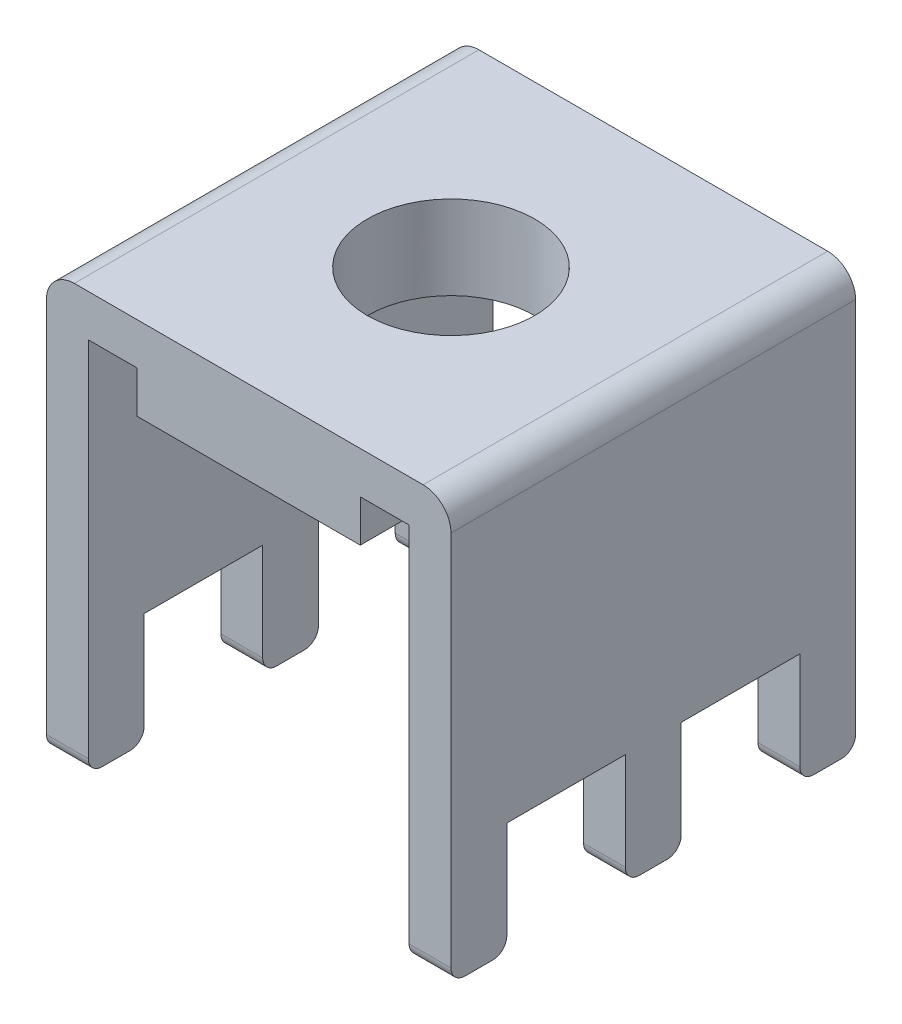
SolidWorks part; units mm, degrees
ref_plane "Front Plane" through (0, 0, 0) normal (0, 0, 1) x (1, 0, 0)
ref_plane "Top Plane" through (0, 0, 0) normal (0, 1, 0) x (1, 0, 0)
ref_plane "Right Plane" through (0, 0, 0) normal (1, 0, 0) x (0, 0, -1)
sketch "Sketch1" plane through (0, 0, 0) normal (0, 0, 1) x (1, 0, 0)
  line L0 (0, 0) -> (-1.5, 0)
  line L1 (-1.5, 0) -> (-1.5, 14)
  line L2 (-0.5, 15) -> (12, 15)
  line L3 (13, 14) -> (13, 0)
  line L4 (13, 0) -> (11.5, 0)
  line L5 (11.5, 0) -> (11.5, 13.5)
  line L6 (11.5, 13.5) -> (9.75, 13.5)
  line L7 (9.75, 13.5) -> (9.75, 12)
  line L8 (9.75, 12) -> (1.75, 12)
  line L9 (1.75, 12) -> (1.75, 13.5)
  line L10 (1.75, 13.5) -> (0, 13.5)
  line L11 (0, 13.5) -> (0, 0)
  arc A0 (12, 15) -> (13, 14) centre (12, 14) cw
  arc A1 (-1.5, 14) -> (-0.5, 15) centre (-0.5, 14) cw
  dimension "D8" = 1
  dimension "D1" = 1.5
  dimension "D2" = 1.5
  dimension "D3" = 14.5
  dimension "D4" = 15
  dimension "D5" = 1.5
  dimension "D6" = 3
  dimension "D7" = 8
extrude "Boss-Extrude1" add sketch "Sketch1" along normal blind 14.5
sketch "Sketch2" plane through (13, 0, 0) normal (1, 0, 0) x (0, 0, -1)
  line L0 (-14.5, 0) -> (0, 0) construction
  line L1 (-12.5, 0) -> (-8.25, 0)
  line L2 (-12.5, 0) -> (-12.5, 4)
  line L3 (-12.5, 4) -> (-8.25, 4)
  line L4 (-8.25, 0) -> (-8.25, 4)
  line L5 (0, 0) -> (0, 14) construction
  line L6 (-6.25, 0) -> (-2, 0)
  line L7 (-6.25, 0) -> (-6.25, 4)
  line L8 (-6.25, 4) -> (-2, 4)
  line L9 (-2, 0) -> (-2, 4)
  line L10 (-14.5, 0) -> (-14.5, 14) construction
  dimension "D1" = 2
  dimension "D2" = 2
  dimension "D3" = 2
  dimension "D4" = 4
extrude "Cut-Extrude1" cut sketch "Sketch2" against normal up to surface (14.5 mm away) up to face at (-1.5, 7, 7.25)
fillet "Fillet1" radius 0.5 12 edges at (-0.75, 0, 14.5) (-0.75, 0, 12.5) (-0.75, 0, 2) (-0.75, 0, 0) (-0.75, 0, 8.25) (-0.75, 0, 6.25) (12.25, 0, 0) (12.25, 0, 6.25) (12.25, 0, 2) (12.25, 0, 8.25) (12.25, 0, 12.5) (12.25, 0, 14.5)
sketch "Sketch3" plane through (0, 15, 0) normal (0, 1, 0) x (1, 0, 0)
  line L0 (-0.5, 0) -> (12, -14.5) construction
  circle A0 centre (5.75, -7.25) radius 3
  point P6 (5.75, -7.25)
  dimension "D1" = 6
extrude "Cut-Extrude2" cut sketch "Sketch3" against normal up to surface (3 mm away) up to face at (5.75, 12, 7.25)
